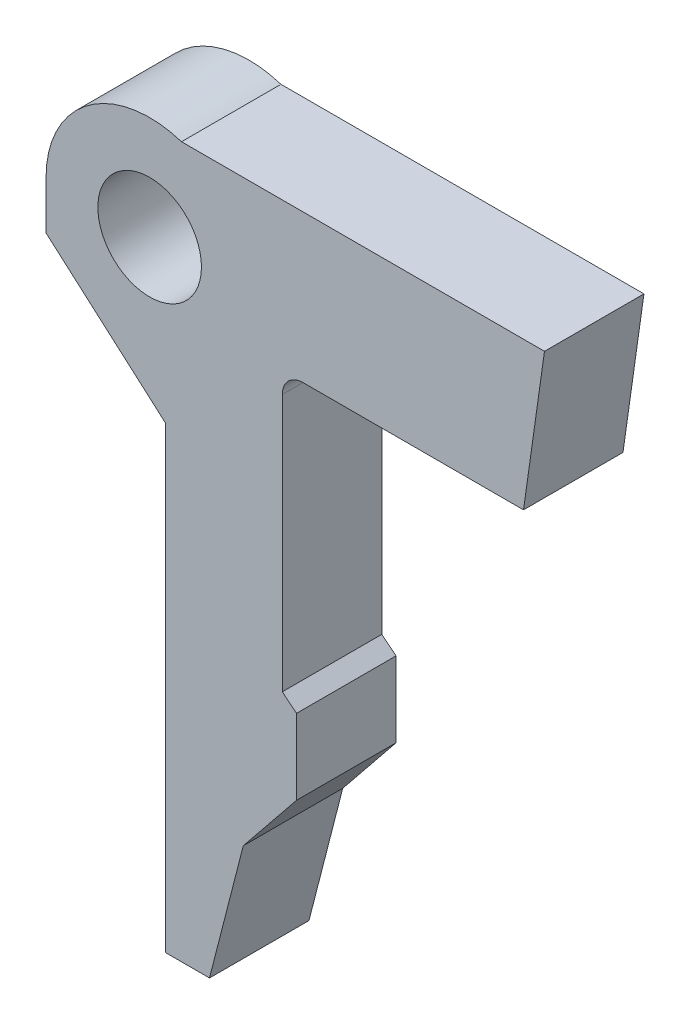
SolidWorks part; units mm, degrees
ref_plane "정면" through (0, 0, 0) normal (0, 0, 1) x (1, 0, 0)
ref_plane "윗면" through (0, 0, 0) normal (0, 1, 0) x (1, 0, 0)
ref_plane "우측면" through (0, 0, 0) normal (1, 0, 0) x (0, 0, -1)
sketch "스케치1" plane through (0, 0, 0) normal (0, 0, 1) x (1, 0, 0)
  line L0 (-5, 0) -> (-5, -2.3265)
  line L1 (0.7542, -29.5199) -> (2.8891, -29.5199)
  line L2 (6.4021, -15.8013) -> (6.4021, -3.3761)
  line L3 (7.4021, -2.3761) -> (18.044, -2.3761)
  line L4 (18.044, -2.3761) -> (19.056, 4.758)
  line L5 (2.8891, -29.5199) -> (4.5185, -23.1774)
  line L6 (-5, -2.3265) -> (0.7542, -7.3778)
  line L7 (0.7542, -7.3778) -> (0.7542, -29.5199)
  line L8 (19.056, 4.758) -> (1.5367, 4.758)
  line L9 (4.5185, -23.1774) -> (7.0899, -19.9903)
  line L10 (7.0899, -19.9903) -> (7.0899, -16.3563)
  line L11 (7.0899, -16.3563) -> (6.4021, -15.8013)
  circle A0 centre (0, 0) radius 2.5
  circle A1 centre (0, 0) radius 5
  arc A3 (6.4021, -3.3761) -> (7.4021, -2.3761) centre (7.4021, -3.3761) cw
  dimension "D1" = 5
  dimension "D2" = 10
  dimension "D3" = 1
extrude "보스-돌출1" add sketch "스케치1" along normal blind 4.8
sketch "스케치3" plane through (0.7542, 0, 0) normal (-1, 0, 0) x (0, 0, 1)
  line L0 (4.8, -29.5199) -> (0, -29.5199) construction
  circle A0 centre (2.4, -27.0199) radius 1.825
  point P2 (2.4, -29.5199)
  dimension "D2" = 3.65
  dimension "D1" = 2.5
extrude "컷-돌출1" cut sketch "스케치3" against normal blind 2
